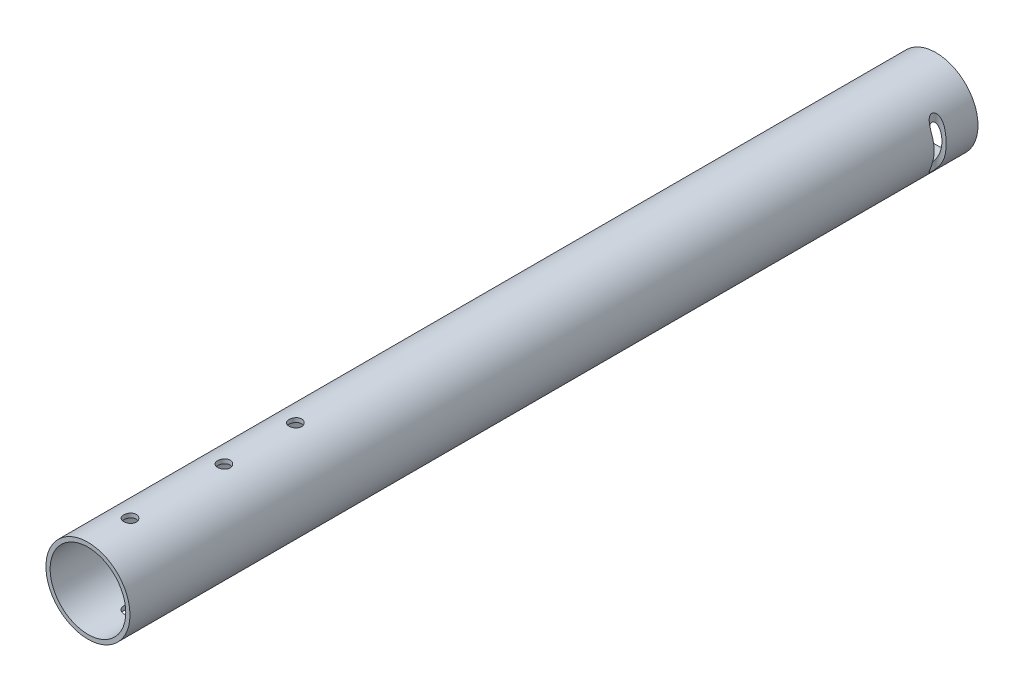
SolidWorks part; units mm, degrees
ref_plane "前视基准面" through (0, 0, 0) normal (0, 0, 1) x (1, 0, 0)
ref_plane "上视基准面" through (0, 0, 0) normal (0, 1, 0) x (1, 0, 0)
ref_plane "右视基准面" through (0, 0, 0) normal (1, 0, 0) x (0, 0, -1)
other "Configuration Table"
sketch "草图1" plane through (0, 0, 0) normal (0, 0, 1) x (1, 0, 0)
  circle A0 centre (0, 0) radius 9
  dimension "D1" = 18
extrude "拉伸-薄壁1" add sketch "草图1" along normal blind 201.8 thin
sketch "草图2" plane through (0, 0, 0) normal (0, 1, 0) x (1, 0, 0)
  line L0 (0, 0) -> (0, -160.96) construction
  line L1 (0, -160.96) -> (50.3159, -160.96) construction
  line L2 (0, -201.8) -> (0, -185.4636) construction
  line L3 (-10, -201.8) -> (10, -201.8) construction
  line L4 (-16.7192, -9) -> (21.1445, -9) construction
  line L5 (9, 0) -> (-9, 0) construction
  circle A0 centre (0, -152.46) radius 1.5
  circle A1 centre (0, -169.46) radius 1.5
  circle A2 centre (0, -191.8) radius 1.5
  circle A3 centre (-9.5, -9) radius 1.5
  circle A4 centre (9.5, -9) radius 1.5
  dimension "D2" = 3
  dimension "D4" = 3
  dimension "D7" = 3
  dimension "D1" = 160.96
  dimension "D3" = 8.5
  dimension "D5" = 10
  dimension "D6" = 9
  dimension "D8" = 9.5
extrude "切除-拉伸1" cut sketch "草图2" against normal mid plane 30
sketch "草图3" plane through (0, 0, 0) normal (1, 0, 0) x (0, 0, -1)
  line L0 (-201.8, 0) -> (0, 0) construction
  line L1 (-201.8, 10) -> (-201.8, -10) construction
  line L3 (-93.4, -3.5) -> (-108.4, -3.5)
  line L4 (-93.4, -3.5) -> (-93.4, 3.5)
  line L5 (-93.4, 3.5) -> (-108.4, 3.5)
  line L6 (-108.4, -3.5) -> (-108.4, 3.5)
  line L7 (-93.4, -3.5) -> (-108.4, 3.5) construction
  line L8 (-93.4, 3.5) -> (-108.4, -3.5) construction
  point P5 (-100.9, 0)
  dimension "D1" = 15
  dimension "D2" = 7
extrude "切除-拉伸2" cut sketch "草图3" against normal blind 10
